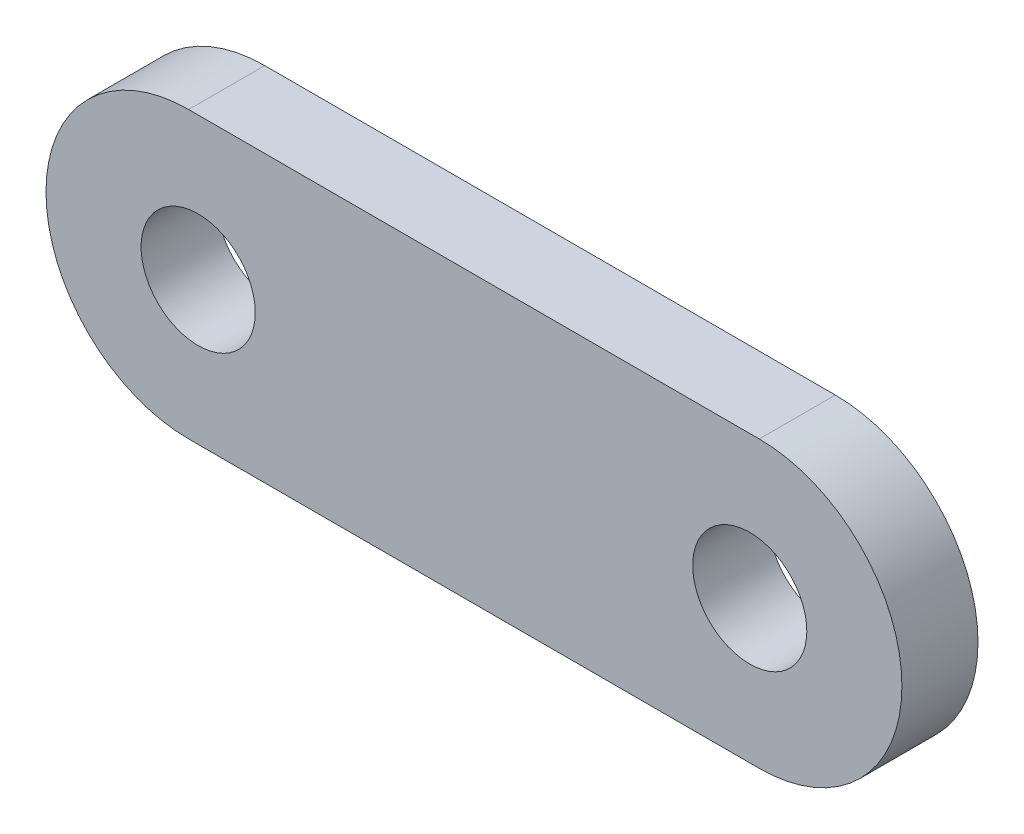
SolidWorks part; units mm, degrees
ref_plane "Спереди" through (0, 0, 0) normal (0, 0, 1) x (1, 0, 0)
ref_plane "Сверху" through (0, 0, 0) normal (0, 1, 0) x (1, 0, 0)
ref_plane "Справа" through (0, 0, 0) normal (1, 0, 0) x (0, 0, -1)
sketch "Эскиз1" plane through (0, 0, 0) normal (0, 0, 1) x (1, 0, 0)
  line L1 (7.4886, 0) -> (37.4886, 0)
  line L3 (7.4886, 15) -> (37.4886, 15)
  circle A0 centre (7.9886, 7.5) radius 3
  circle A1 centre (36.9886, 7.5) radius 3
  arc A2 (7.4886, 15) -> (7.4886, 0) centre (7.4886, 7.5) ccw
  arc A3 (37.4886, 0) -> (37.4886, 15) centre (37.4886, 7.5) ccw
  dimension "D3" = 6
  dimension "D4" = 6
  dimension "D7" = 0.5
  dimension "D1" = 30
  dimension "D5" = 7.5
  dimension "D6" = 7.5
  dimension "D8" = 0.5
extrude "Бобышка-Вытянуть1" add sketch "Эскиз1" along normal blind 4
